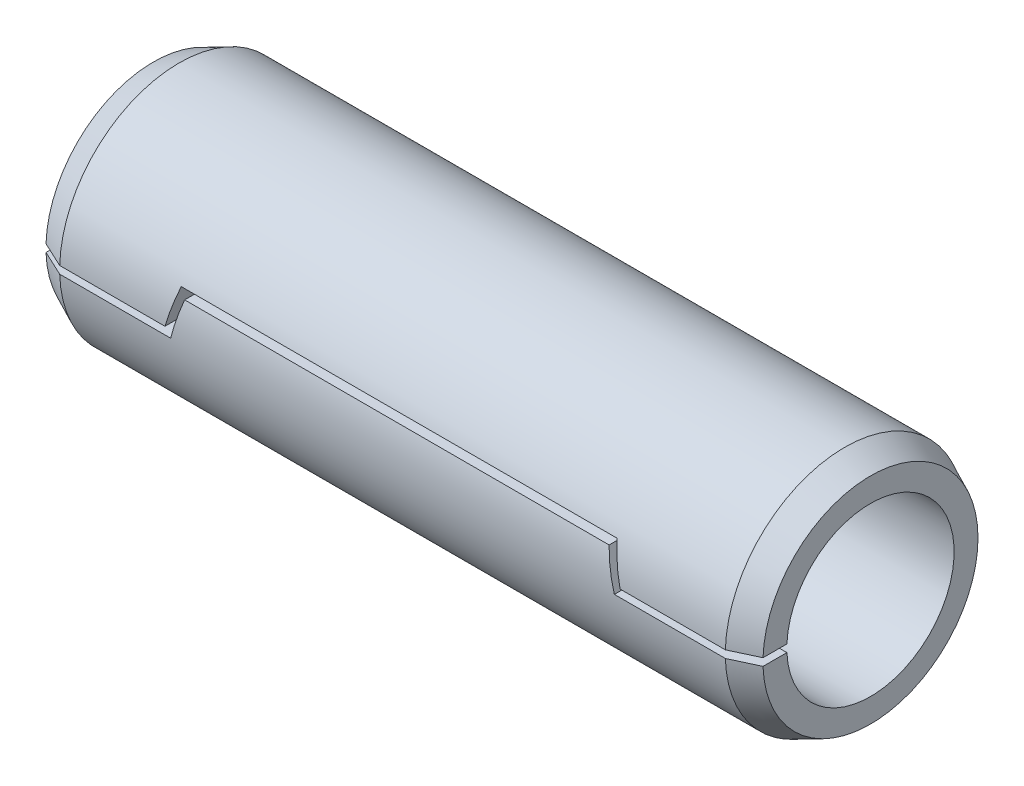
SolidWorks part; units mm, degrees
material "Plain Carbon Steel"
ref_plane "Front" through (0, 0, 0) normal (0, 0, 1) x (1, 0, 0)
ref_plane "Top" through (0, 0, 0) normal (0, 1, 0) x (1, 0, 0)
ref_plane "Right" through (0, 0, 0) normal (1, 0, 0) x (0, 0, -1)
sketch "Sketch1" plane through (0, 0, 0) normal (0, 0, 1) x (1, 0, 0)
  line L0 (-12, 0) -> (12, 0) construction
  line L1 (-12, 2.8) -> (12, 2.8)
  line L2 (12, 2.8) -> (12, 3.5992)
  line L3 (12, 3.5992) -> (11.1405, 4)
  line L4 (11.1405, 4) -> (-11.1405, 4)
  line L5 (-11.1405, 4) -> (-12, 3.5992)
  line L6 (-12, 3.5992) -> (-12, 2.8)
  line L7 (0, 4) -> (0, 2.8) construction
  dimension "L" = 24
  dimension "T" = 1.2
  dimension "OD" = 8
  dimension "D4" = 25
  dimension "D1" = 0.7992
revolve "Revolve1" add sketch "Sketch1" angle 360 about L0
sketch "Sketch2" plane through (0, 0, 0) normal (0, 0, 1) x (1, 0, 0)
  line L0 (-12, 0) -> (-7.5215, 0)
  line L1 (-7.5215, 0) -> (-7.2, 1.2)
  line L2 (-7.2, 1.2) -> (7.2, 1.2)
  line L3 (7.2, 1.2) -> (7.5215, 0)
  line L4 (7.5215, 0) -> (12, 0)
  line L5 (-12, 3.5992) -> (-12, -3.5992) construction
  line L6 (12, -3.5992) -> (12, 3.5992) construction
  line L7 (0, 0) -> (0, 1.2) construction
  dimension "D1" = 15
  dimension "D2" = 1.2
  dimension "D3" = 14.4
extrude "Cut-Extrude-Thin1" cut sketch "Sketch2" along normal through all thin thin type mid plane wall 0.25
sketch "Sketch3" plane through (-12, 0, 0) normal (-1, 0, 0) x (0, 0, 1)
  circle A0 centre (0, 0) radius 4
  arc A1 (3.998, 0.125) -> (3.998, -0.125) centre (0, 0) ccw construction
equation "\"D1@Sketch1\" = \"T@Sketch1\"*.666"
equation "\"D2@Sketch2\" = \"T@Sketch1\""
equation "\"D3@Sketch2\" = \"L@Sketch1\"*.6"
